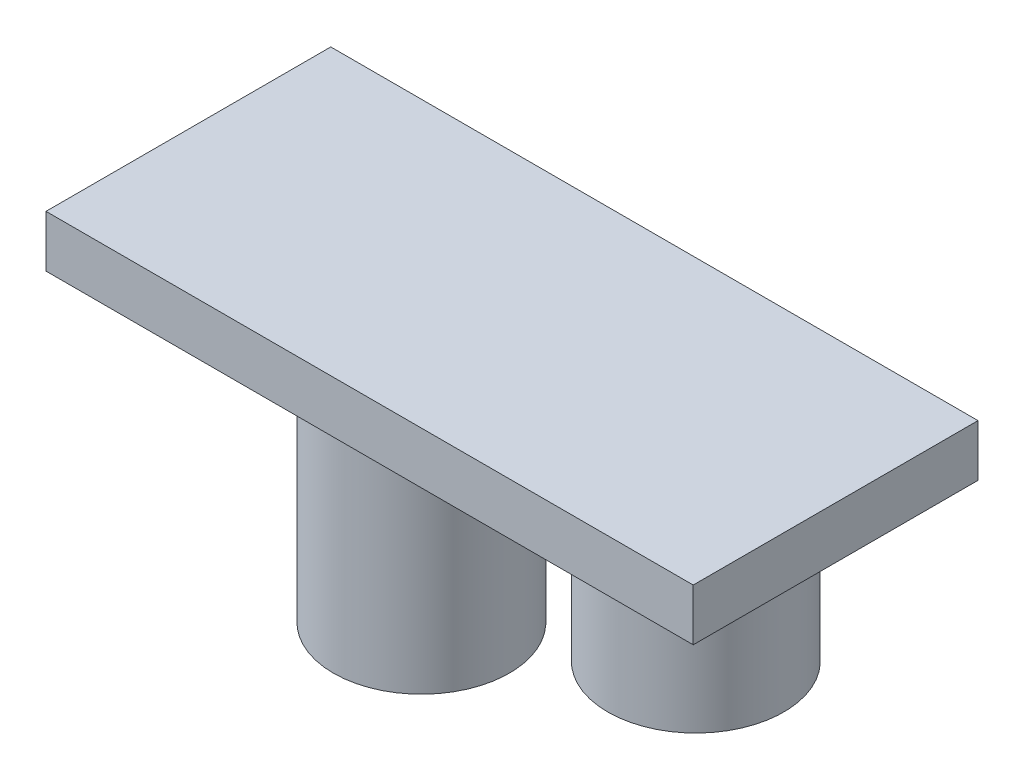
SolidWorks part; units mm, degrees
ref_plane "前视基准面" through (0, 0, 0) normal (0, 0, 1) x (1, 0, 0)
ref_plane "上视基准面" through (0, 0, 0) normal (0, 1, 0) x (1, 0, 0)
ref_plane "右视基准面" through (0, 0, 0) normal (1, 0, 0) x (0, 0, -1)
sketch "草图2" plane through (0, 0, 0) normal (0, 1, 0) x (1, 0, 0)
  circle A0 centre (0, 0) radius 1.7
  dimension "D1" = 3.4
extrude "凸台-拉伸1" add sketch "草图2" against normal blind 5
sketch "草图9" plane through (0, 0, 0) normal (0, 1, 0) x (1, 0, 0)
  line L5 (-4.5, -2.75) -> (8, -2.75)
  line L6 (6.25, -2.75) -> (-6.25, 2.75) construction
  line L7 (-4.5, -2.75) -> (-4.5, 2.75)
  line L8 (-4.5, 2.75) -> (8, 2.75)
  line L9 (8, -2.75) -> (8, 2.75)
  dimension "D1" = 12.5
  dimension "D3" = 5.5
  dimension "D4" = 4.5
  dimension "D5" = 2.75
extrude "凸台-拉伸5" add sketch "草图9" along normal blind 1
sketch "草图10" plane through (0, 0, 0) normal (0, -1, 0) x (1, 0, 0)
  circle A0 centre (0, 0) radius 1.7 construction
  arc A1 (5.3, -1.7) -> (5.3, 1.7) centre (5.3, 0) ccw
  circle A2 centre (0, 0) radius 1.7
  circle A4 centre (5.3, 0) radius 1.7
  dimension "D3" = 1.7
sketch "草图11" plane through (0, 0, 0) normal (0, -1, 0) x (1, 0, 0)
  circle A0 centre (5.3, 0) radius 1.7
  dimension "D1" = 3.4
extrude "凸台-拉伸6" add sketch "草图11" along normal blind 3
